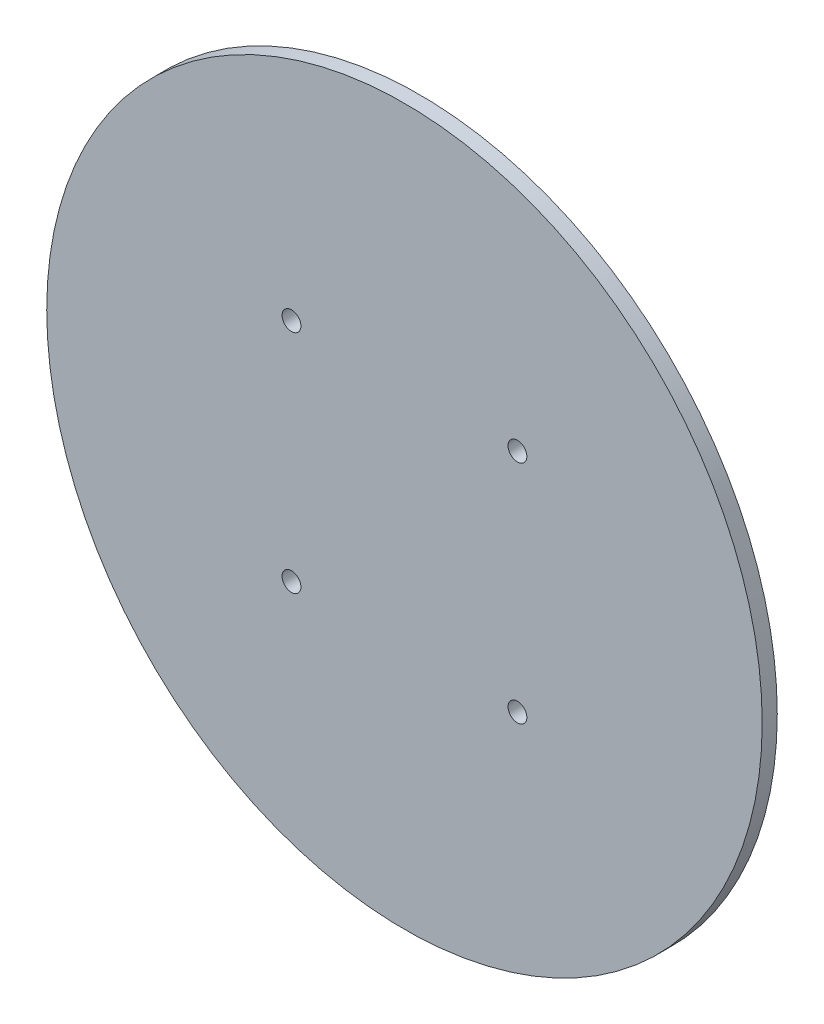
SolidWorks part; units mm, degrees
ref_plane "Alzado" through (0, 0, 0) normal (0, 0, 1) x (1, 0, 0)
ref_plane "Planta" through (0, 0, 0) normal (0, 1, 0) x (1, 0, 0)
ref_plane "Vista lateral" through (0, 0, 0) normal (1, 0, 0) x (0, 0, -1)
sketch "Croquis1" plane through (0, 0, 0) normal (0, 0, 1) x (1, 0, 0)
  circle A0 centre (0, 0) radius 95
  dimension "D1" = 190
extrude "Saliente-Extruir1" add sketch "Croquis1" along normal blind 4
sketch "Croquis2" plane through (0, 0, 4) normal (0, 0, 1) x (1, 0, 0)
  circle A0 centre (-30, 30) radius 2.5
  circle A1 centre (30, 30) radius 2.5
  circle A2 centre (-30, -30) radius 2.5
  circle A3 centre (30, -30) radius 2.5
  dimension "D1" = 5
  dimension "D2" = 30
  dimension "D3" = 5
  dimension "D4" = 30
  dimension "D5" = 30
  dimension "D7" = 5
  dimension "D8" = 30
  dimension "D9" = 5
  dimension "D6" = 30
extrude "Cortar-Extruir1" cut sketch "Croquis2" against normal blind 4
